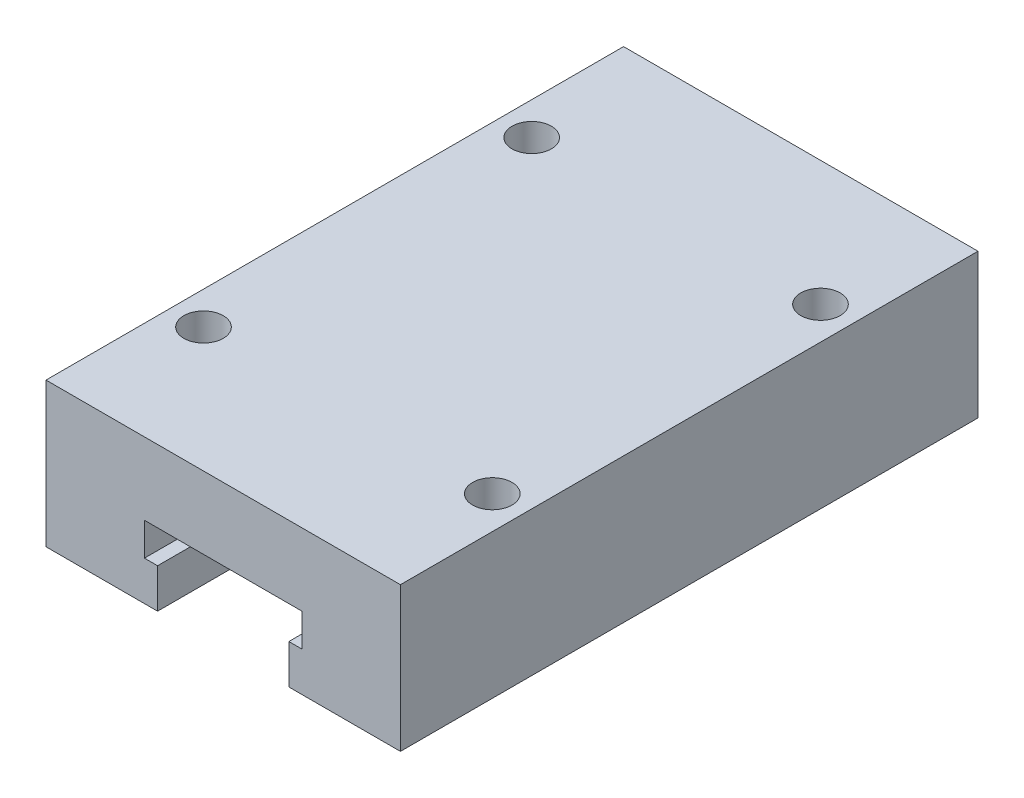
SolidWorks part; units mm, degrees
ref_plane "Front Plane" through (0, 0, 0) normal (0, 0, 1) x (1, 0, 0)
ref_plane "Top Plane" through (0, 0, 0) normal (0, 1, 0) x (1, 0, 0)
ref_plane "Right Plane" through (0, 0, 0) normal (1, 0, 0) x (0, 0, -1)
sketch "Sketch1" plane through (0, 0, 0) normal (0, 0, 1) x (1, 0, 0)
  line L0 (19.5, 5.5) -> (19.5, 3)
  line L3 (7.5, 5.5) -> (19.5, 5.5)
  line L4 (19.5, 3) -> (18.5, 3)
  line L5 (18.5, 3) -> (18.5, 0)
  line L8 (7.5, 5.5) -> (7.5, 3)
  line L9 (7.5, 3) -> (8.5, 3)
  line L10 (8.5, 3) -> (8.5, 0)
  line L13 (0, 0) -> (8.5, 0)
  line L14 (0, 0) -> (0, 11)
  line L15 (0, 11) -> (27, 11)
  line L16 (27, 11) -> (27, 0)
  line L17 (27, 0) -> (18.5, 0)
  point P0 (0, 0)
  dimension "D1" = 12
  dimension "D2" = 11
  dimension "D3" = 1
  dimension "D4" = 2.5
  dimension "D5" = 27
  dimension "D6" = 3
extrude "Boss-Extrude1" add sketch "Sketch1" along normal blind 44
sketch "Sketch2" plane through (0, 11, 0) normal (0, 1, 0) x (1, 0, 0)
  line L0 (27, -44) -> (27, 0) construction
  line L1 (0, -44) -> (0, 0) construction
  line L2 (24.5, -9.5) -> (24.5, -34.5) construction
  circle A0 centre (2.5, -9.5) radius 1.5
  circle A1 centre (24.5, -9.5) radius 1.5
  circle A2 centre (24.5, -34.5) radius 1.5
  circle A3 centre (2.5, -34.5) radius 1.5
  point P8 (27, -22)
  point P9 (24.5, -22)
  dimension "D1" = 3
  dimension "D2" = 2.5
  dimension "D3" = 2.5
  dimension "D4" = 25
extrude "Cut-Extrude1" cut sketch "Sketch2" against normal blind 4
